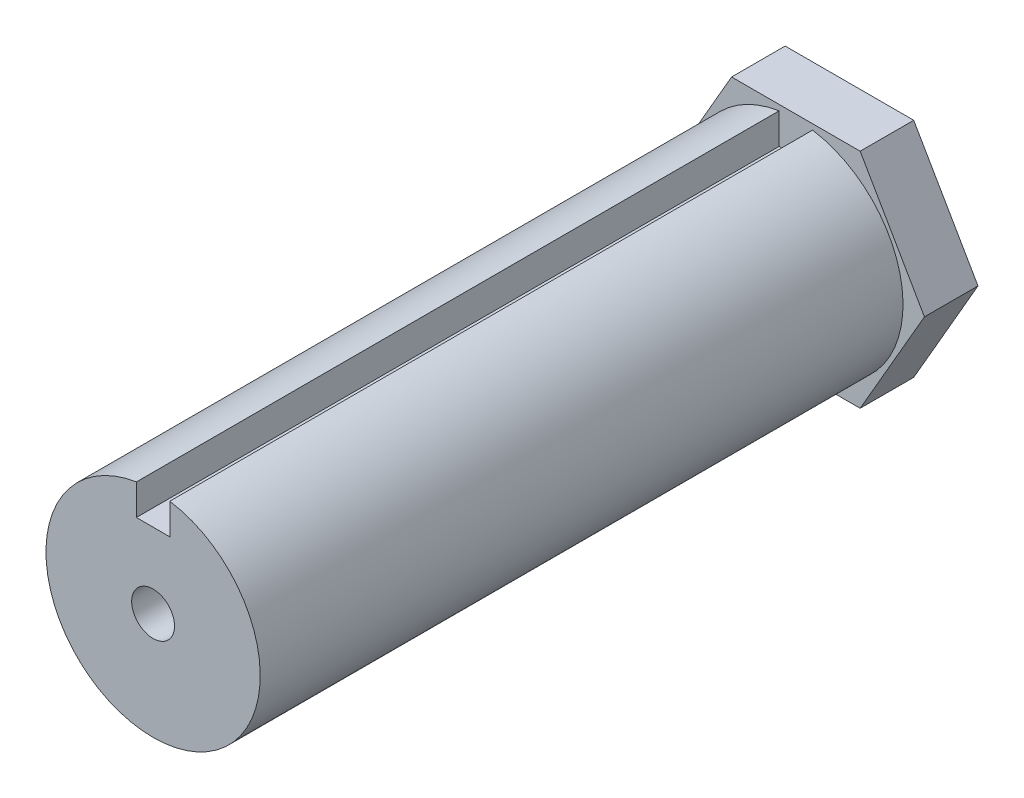
SolidWorks part; units mm, degrees
ref_plane "Front Plane" through (0, 0, 0) normal (0, 0, 1) x (1, 0, 0)
ref_plane "Top Plane" through (0, 0, 0) normal (0, 1, 0) x (1, 0, 0)
ref_plane "Right Plane" through (0, 0, 0) normal (1, 0, 0) x (0, 0, -1)
sketch "Sketch3" plane through (0, 0, 0) normal (0, 0, 1) x (1, 0, 0)
  line L1 (6, 10.3923) -> (-6, 10.3923)
  line L2 (-6, 10.3923) -> (-12, 0)
  line L3 (-12, 0) -> (-6, -10.3923)
  line L4 (-6, -10.3923) -> (6, -10.3923)
  line L5 (6, -10.3923) -> (12, 0)
  line L6 (12, 0) -> (6, 10.3923)
  circle A0 centre (0, 0) radius 10.3923 construction
  dimension "D1" = 12
extrude "Boss-Extrude3" add sketch "Sketch3" along normal blind 5
sketch "Sketch5" plane through (0, 0, 5) normal (0, 0, 1) x (1, 0, 0)
  circle A0 centre (0, 0) radius 10
  dimension "D1" = 20
extrude "Boss-Extrude4" add sketch "Sketch5" along normal blind 60
sketch "Sketch6" plane through (0, 0, 65) normal (0, 0, 1) x (1, 0, 0)
  circle A0 centre (0, 0) radius 2
  dimension "D1" = 4
extrude "Cut-Extrude1" cut sketch "Sketch6" against normal blind 20
sketch "Sketch9" plane through (0, 0, 65) normal (0, 0, 1) x (1, 0, 0)
  line L1 (-1.5597, 7) -> (1.5597, 7)
  line L2 (-1.5597, 7) -> (-1.5597, 14.0652)
  line L3 (-1.5597, 14.0652) -> (1.5597, 14.0652)
  line L4 (1.5597, 7) -> (1.5597, 14.0652)
  line L5 (-1.5597, 7) -> (1.5597, 14.0652) construction
  line L6 (-1.5597, 14.0652) -> (1.5597, 7) construction
  circle A0 centre (0, 0) radius 10 construction
  point P0 (0, 10.5326)
  point P5 (0, 7)
  dimension "D1" = 7
extrude "Cut-Extrude3" cut sketch "Sketch9" against normal blind 60
